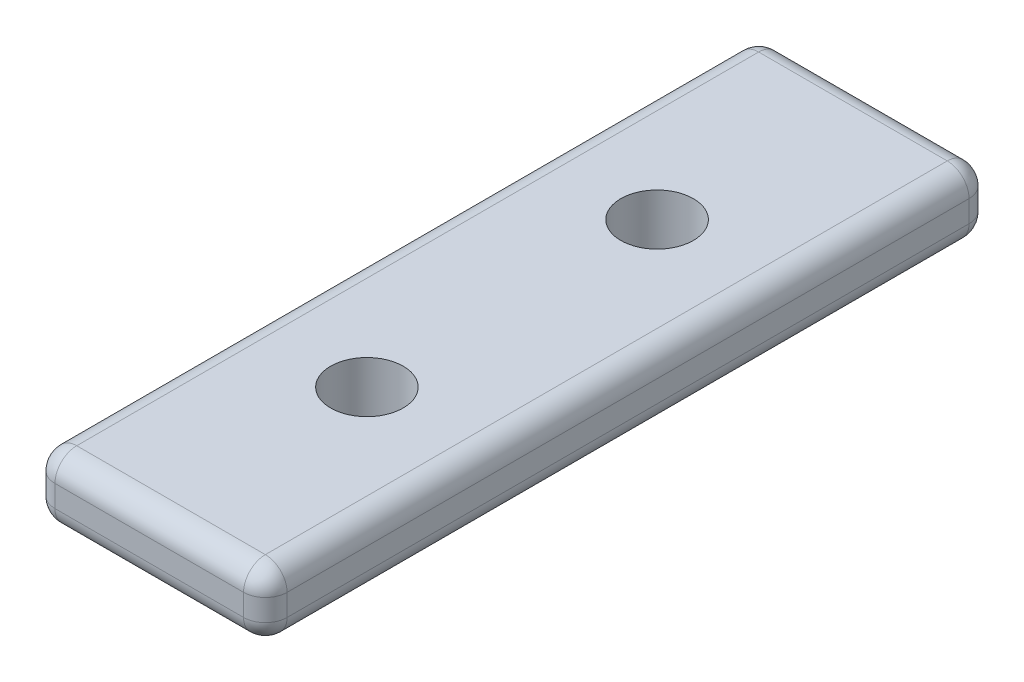
SolidWorks part; units mm, degrees
material "Rubber"
ref_plane "Front Plane" through (0, 0, 0) normal (0, 0, 1) x (1, 0, 0)
ref_plane "Top Plane" through (0, 0, 0) normal (0, 1, 0) x (1, 0, 0)
ref_plane "Right Plane" through (0, 0, 0) normal (1, 0, 0) x (0, 0, -1)
sketch "Sketch1" plane through (0, 0, 0) normal (0, 0, 1) x (1, 0, 0)
  line L1 (-8, 2.25) -> (8, 2.25)
  line L2 (-8, 2.25) -> (-8, -2.25)
  line L3 (-8, -2.25) -> (8, -2.25)
  line L4 (8, 2.25) -> (8, -2.25)
  line L5 (-8, 2.25) -> (8, -2.25) construction
  line L6 (-8, -2.25) -> (8, 2.25) construction
  point P0 (0, 0)
extrude "Boss-Extrude1" add sketch "Sketch1" along normal blind 50
fillet "Fillet1" radius 1.5 12 edges at (-8, 0, 50) (8, 0, 50) (0, 2.25, 50) (0, -2.25, 50) (-8, -2.25, 25) (8, -2.25, 25) (-8, 0, 0) (0, -2.25, 0) (8, 0, 0) (0, 2.25, 0) (-8, 2.25, 25) (8, 2.25, 25)
sketch "Sketch2" plane through (0, -2.25, 0) normal (0, -1, 0) x (1, 0, 0)
  circle A0 centre (0, 15) radius 2.5
  circle A1 centre (0, 35) radius 2.5
extrude "Cut-Extrude1" cut sketch "Sketch2" against normal blind 5
